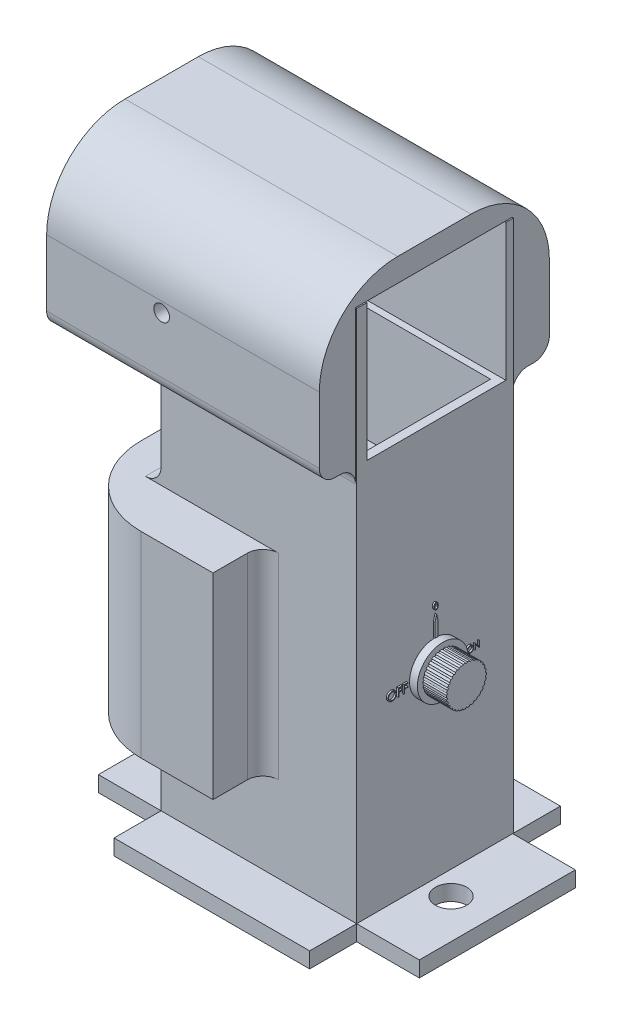
SolidWorks part; units mm, degrees
ref_plane "Front Plane" through (0, 0, 0) normal (0, 0, 1) x (1, 0, 0)
ref_plane "Top Plane" through (0, 0, 0) normal (0, 1, 0) x (1, 0, 0)
ref_plane "Right Plane" through (0, 0, 0) normal (1, 0, 0) x (0, 0, -1)
sketch "Sketch1" plane through (0, 0, 0) normal (0, 1, 0) x (1, 0, 0)
  line L1 (-62.395, -50) -> (62.395, -50)
  line L2 (-62.395, -50) -> (-62.395, 50)
  line L3 (-62.395, 50) -> (62.395, 50)
  line L4 (62.395, -50) -> (62.395, 50)
  line L5 (-62.395, -50) -> (62.395, 50) construction
  line L6 (-62.395, 50) -> (62.395, -50) construction
  point P0 (0, 0)
  dimension "D1" = 124.79
  dimension "D2" = 100
extrude "Boss-Extrude1" add sketch "Sketch1" along normal blind 350
sketch "Sketch2" plane through (0, 0, 50) normal (0, 0, 1) x (1, 0, 0)
  line L0 (62.395, 350) -> (62.395, 0) construction
  line L1 (-62.395, 0) -> (62.395, 0)
  line L2 (-62.395, 0) -> (-62.395, 10)
  line L3 (-62.395, 10) -> (62.395, 10)
  line L4 (62.395, 0) -> (62.395, 10)
  dimension "D1" = 10
extrude "Boss-Extrude2" add sketch "Sketch2" along normal blind 30
sketch "Sketch3" plane through (0, 0, -50) normal (0, 0, -1) x (-1, 0, 0)
  line L0 (62.395, 350) -> (62.395, 0) construction
  line L1 (-62.395, 0) -> (62.395, 0)
  line L2 (-62.395, 0) -> (-62.395, 10)
  line L3 (-62.395, 10) -> (62.395, 10)
  line L4 (62.395, 0) -> (62.395, 10)
  dimension "D1" = 10
extrude "Boss-Extrude3" add sketch "Sketch3" along normal blind 30
sketch "Sketch6" plane through (62.395, 0, 0) normal (1, 0, 0) x (0, 0, -1)
  line L0 (-80, 0) -> (80, 0) construction
  line L1 (-50, 10) -> (49.554, 10)
  line L2 (-50, 10) -> (-50, 0)
  line L3 (-50, 0) -> (49.554, 0)
  line L4 (49.554, 10) -> (49.554, 0)
extrude "Boss-Extrude4" add sketch "Sketch6" along normal blind 40
sketch "Sketch7" plane through (-62.395, 0, 0) normal (-1, 0, 0) x (0, 0, 1)
  line L0 (-80, 0) -> (80, 0) construction
  line L1 (-50, 10) -> (50, 10)
  line L2 (-50, 10) -> (-50, 0)
  line L3 (-50, 0) -> (50, 0)
  line L4 (50, 10) -> (50, 0)
extrude "Boss-Extrude5" add sketch "Sketch7" along normal blind 40
sketch "Sketch8" plane through (0, 10, 0) normal (0, 1, 0) x (1, 0, 0)
  circle A0 centre (-82.395, 0) radius 10
extrude "Cut-Extrude3" cut sketch "Sketch8" against normal blind 40
sketch "Sketch10" plane through (0, 0, 0) normal (0, -1, 0) x (1, 0, 0)
  circle A0 centre (77.326, 4.7064) radius 10
extrude "Cut-Extrude5" cut sketch "Sketch10" against normal blind 10
sketch "Sketch11" plane through (-62.395, 0, 0) normal (-1, 0, 0) x (0, 0, 1)
  line L0 (-50, 350) -> (50, 350) construction
  line L1 (-45.2016, 350) -> (43.3916, 350)
  line L2 (-45.2016, 350) -> (-45.2016, 262.6872)
  line L3 (-45.2016, 262.6872) -> (43.3916, 262.6872)
  line L4 (43.3916, 350) -> (43.3916, 262.6872)
extrude "Cut-Extrude6" cut sketch "Sketch11" against normal blind 147
sketch "Sketch12" plane through (0, 0, -50) normal (0, 0, -1) x (-1, 0, 0)
  circle A0 centre (0, 325.5125) radius 10
extrude "Cut-Extrude7" cut sketch "Sketch12" against normal blind 147
sketch "Sketch13" plane through (0, 0, 0) normal (0, -1, 0) x (-1, 0, 0)
  line L1 (56.895, 40.9218) -> (-56.895, 40.9218)
  line L2 (56.895, 40.9218) -> (56.895, -40.9218)
  line L3 (56.895, -40.9218) -> (-56.895, -40.9218)
  line L4 (-56.895, 40.9218) -> (-56.895, -40.9218)
  line L5 (56.895, 40.9218) -> (-56.895, -40.9218) construction
  line L6 (56.895, -40.9218) -> (-56.895, 40.9218) construction
  point P0 (0, 0)
extrude "Cut-Extrude8" cut sketch "Sketch13" against normal blind 362
sketch "Sketch15" plane through (-62.395, 0, 0) normal (-1, 0, 0) x (0, 0, 1)
  line L1 (-73.759, 364.8522) -> (73.0173, 364.8522)
  line L2 (-73.759, 364.8522) -> (-73.759, 262.6872)
  line L3 (-73.759, 262.6872) -> (73.0173, 262.6872)
  line L4 (73.0173, 364.8522) -> (73.0173, 262.6872)
  line L5 (-45.2016, 350) -> (43.3916, 350)
  line L6 (-45.2016, 350) -> (-45.2016, 262.6872)
  line L7 (-45.2016, 262.6872) -> (43.3916, 262.6872)
  line L8 (43.3916, 350) -> (43.3916, 262.6872)
  line M3 (-45.2016, 350) -> (-50, 350)
  line M4 (-50, 350) -> (-50, 10)
  line M6 (50, 10) -> (50, 350)
  line M7 (50, 350) -> (43.3916, 350)
extrude "Boss-Extrude6" add sketch "Sketch15" against normal blind 124 and the other way blind 50 contours L5 L3 L4 L1 L2 M3 M7 M6 M4
fillet "Fillet1" radius 10 1 edges at (-0.395, 262.6872, -50)
fillet "Fillet2" radius 10 1 edges at (-0.395, 262.6872, 50)
sketch "Sketch16" plane through (0, 0, 73.0173) normal (0, 0, 1) x (1, 0, 0)
  circle A0 centre (-38.9958, 308.3493) radius 5
extrude "Cut-Extrude9" cut sketch "Sketch16" against normal blind 153
fillet "Fillet4" radius 50 2 edges at (-25.395, 364.8522, 73.0173) (-25.395, 364.8522, -73.759)
fillet "Fillet5" radius 10 2 edges at (-25.395, 262.6872, -73.759) (-25.395, 262.6872, 73.0173)
sketch "Sketch18" plane through (-62.395, 0, 0) normal (-1, 0, 0) x (0, 0, 1)
  line L1 (-85.3364, 189.8602) -> (81.8675, 189.8602)
  line L2 (-85.3364, 189.8602) -> (-85.3364, 64.5982)
  line L3 (-85.3364, 64.5982) -> (81.8675, 64.5982)
  line L4 (81.8675, 189.8602) -> (81.8675, 64.5982)
extrude "Boss-Extrude7" add sketch "Sketch18" against normal blind 65 and the other way blind 31
fillet "Fillet6" radius 10 1 edges at (2.605, 127.2292, -50)
fillet "Fillet7" radius 10 1 edges at (2.605, 127.2292, 50)
fillet "Fillet8" radius 10 1 edges at (-62.395, 189.8602, 0)
fillet "Fillet9" radius 10 1 edges at (-62.395, 64.5982, 0)
fillet "Fillet10" radius 50 1 edges at (-93.395, 127.2292, -85.3364)
fillet "Fillet11" radius 50 1 edges at (-93.395, 127.2292, 81.8675)
sketch "Sketch19" plane through (0, 0, 0) normal (0, -1, 0) x (-1, 0, 0)
  circle A0 centre (66.3643, 0) radius 4.1333
  circle A1 centre (66.3643, -15.2758) radius 4.1333
  circle A2 centre (66.3643, -7.8564) radius 2.8792
extrude "Boss-Extrude8" add sketch "Sketch19" against normal up to vertex (262.6872 mm away)
sketch "Sketch20" plane through (62.395, 0, 0) normal (1, 0, 0) x (0, 0, -1)
  circle A0 centre (0, 126.7912) radius 16.2442
extrude "Boss-Extrude9" add sketch "Sketch20" along normal blind 5
sketch "Sketch21" plane through (67.395, 0, 0) normal (1, 0, 0) x (0, 0, -1)
  circle A0 centre (0, 126.7912) radius 12.731
  point P3 (0, 0)
extrude "Boss-Extrude10" add sketch "Sketch21" along normal blind 15
sketch "Sketch22" plane through (82.395, 0, 0) normal (1, 0, 0) x (0, 0, -1)
  circle A0 centre (0, 139.5222) radius 0.5734
  circle A1 centre (0, 126.7912) radius 12.731 construction
  circle A2 centre (0, 126.7912) radius 12.731 construction
  circle A3 centre (2.6469, 139.244) radius 0.5734
  circle A4 centre (5.1782, 138.4215) radius 0.5734
  circle A5 centre (7.4831, 137.0908) radius 0.5734
  circle A6 centre (9.461, 135.3099) radius 0.5734
  circle A7 centre (11.0254, 133.1567) radius 0.5734
  circle A8 centre (12.1079, 130.7253) radius 0.5734
  circle A9 centre (12.6612, 128.1219) radius 0.5734
  circle A10 centre (12.6612, 125.4604) radius 0.5734
  circle A11 centre (12.1079, 122.8571) radius 0.5734
  circle A12 centre (11.0254, 120.4257) radius 0.5734
  circle A13 centre (9.461, 118.2725) radius 0.5734
  circle A14 centre (7.4831, 116.4916) radius 0.5734
  circle A15 centre (5.1782, 115.1609) radius 0.5734
  circle A16 centre (2.6469, 114.3384) radius 0.5734
  circle A17 centre (0, 114.0602) radius 0.5734
  circle A18 centre (-2.6469, 114.3384) radius 0.5734
  circle A19 centre (-5.1782, 115.1609) radius 0.5734
  circle A20 centre (-7.4831, 116.4916) radius 0.5734
  circle A21 centre (-9.461, 118.2725) radius 0.5734
  circle A22 centre (-11.0254, 120.4257) radius 0.5734
  circle A23 centre (-12.1079, 122.8571) radius 0.5734
  circle A24 centre (-12.6612, 125.4604) radius 0.5734
  circle A25 centre (-12.6612, 128.1219) radius 0.5734
  circle A26 centre (-12.1079, 130.7253) radius 0.5734
  circle A27 centre (-11.0254, 133.1567) radius 0.5734
  circle A28 centre (-9.461, 135.3099) radius 0.5734
  circle A29 centre (-7.4831, 137.0908) radius 0.5734
  circle A30 centre (-5.1782, 138.4215) radius 0.5734
  circle A31 centre (-2.6469, 139.244) radius 0.5734
  point P67 (0, 126.7912)
  dimension "D1" = 30
extrude "Cut-Extrude10" cut sketch "Sketch22" against normal blind 15
sketch "Sketch23" plane through (62.395, 0, 0) normal (1, 0, 0) x (0, 0, -1)
  text T0 "OFF" font "Century Gothic" height in points 20
extrude "Boss-Extrude11" add sketch "Sketch23" along normal blind 1
sketch "Sketch24" plane through (62.395, 0, 0) normal (1, 0, 0) x (0, 0, -1)
  text T0 "ON" font "Century Gothic" height in points 15
extrude "Boss-Extrude12" add sketch "Sketch24" along normal blind 1
sketch "Sketch25" plane through (62.395, 0, 0) normal (1, 0, 0) x (0, 0, -1)
  line L0 (-0.9137, 152.7795) -> (0, 156.6765)
  line L2 (-0.9137, 152.7795) -> (-0.9137, 143.6863)
  line L3 (-0.9137, 143.6863) -> (0.9137, 143.6863)
  line L4 (0.9137, 152.7795) -> (0.9137, 143.6863)
  line L5 (-0.9137, 152.7795) -> (0.9137, 143.6863) construction
  line L6 (-0.9137, 143.6863) -> (0.9137, 152.7795) construction
  line L7 (0, 156.6765) -> (0.9137, 152.7795)
  point P0 (0, 148.2329)
extrude "Boss-Extrude13" add sketch "Sketch25" along normal blind 1
sketch "Sketch26" plane through (62.395, 0, 0) normal (1, 0, 0) x (0, 0, -1)
  text T0 "0" font "Century Gothic" height in points 15
extrude "Boss-Extrude14" add sketch "Sketch26" along normal blind 1
